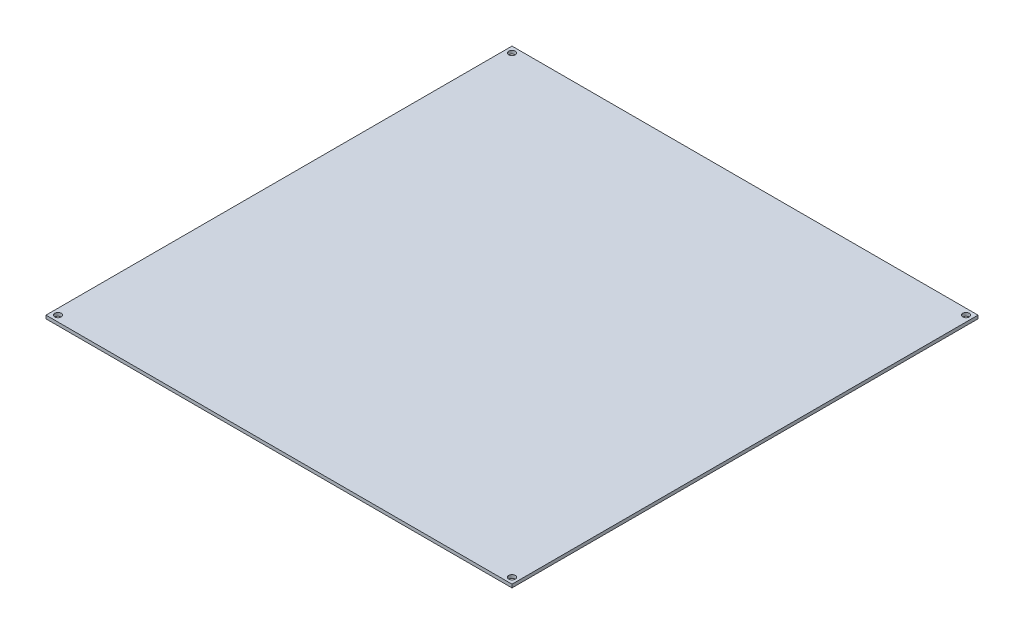
SolidWorks part; units mm, degrees
material "Placa de circuito impreso"
ref_plane "Alzado" through (0, 0, 0) normal (0, 0, 1) x (1, 0, 0)
ref_plane "Planta" through (0, 0, 0) normal (0, 1, 0) x (1, 0, 0)
ref_plane "Vista lateral" through (0, 0, 0) normal (1, 0, 0) x (0, 0, -1)
sketch "Croquis1" plane through (0, 0, 0) normal (0, 1, 0) x (1, 0, 0)
  line L1 (-125.0431, 61.6824) -> (88.9569, 61.6824)
  line L2 (-125.0431, 61.6824) -> (-125.0431, -152.3176)
  line L3 (-125.0431, -152.3176) -> (88.9569, -152.3176)
  line L4 (88.9569, 61.6824) -> (88.9569, -152.3176)
  circle A0 centre (-122.2931, 58.9324) radius 1.5
  circle A1 centre (86.2069, 58.9324) radius 1.5
  circle A2 centre (-122.2931, -149.5676) radius 1.5
  circle A3 centre (86.2069, -149.5676) radius 1.5
  dimension "D2" = 3
  dimension "D3" = 208.5
  dimension "D4" = 208.5
  dimension "D5" = 208.5
  dimension "D6" = 208.5
  dimension "D7" = 2.75
  dimension "D8" = 2.75
  dimension "D9" = 2.75
  dimension "D1" = 214
extrude "Saliente-Extruir2" add sketch "Croquis1" along normal blind 1.5
